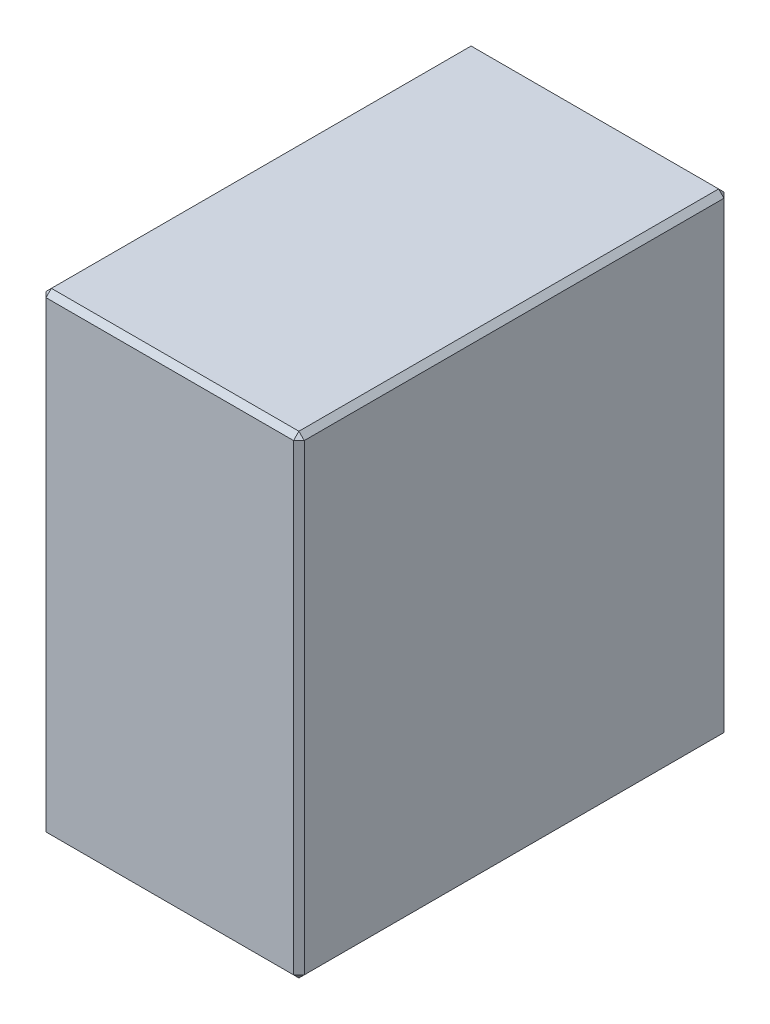
SolidWorks part; units mm, degrees
ref_plane "Front Plane" through (0, 0, 0) normal (0, 0, 1) x (1, 0, 0)
ref_plane "Top Plane" through (0, 0, 0) normal (0, 1, 0) x (1, 0, 0)
ref_plane "Right Plane" through (0, 0, 0) normal (1, 0, 0) x (0, 0, -1)
sketch "Sketch1" plane through (0, 0, 0) normal (1, 0, 0) x (0, 0, -1)
  line L0 (0, 0) -> (20, 0)
  line L1 (20, 0) -> (20, 22)
  line L2 (20, 22) -> (0, 22)
  line L3 (0, 22) -> (0, 0)
extrude "Boss-Extrude1" add sketch "Sketch1" against normal blind 12
hole_wizard "Hole1" positions "Sketch3" profile "Sketch2" legacy
sketch "Sketch3" plane through (0, 0, -20) normal (0, 0, -1) x (-1, 0, 0)
  point P0 (6, 17)
sketch "Sketch2" plane through (-6, 17, -20) normal (1, 0, 0) x (0, 1, 0)
  line L0 (0, 0) -> (0, 12.4781)
  line L1 (0, 12.4781) -> (2.46, 11)
  line L2 (2.46, 11) -> (2.46, 0)
  line L4 (2.46, 0) -> (0, 0)
  line L6 (0, 12.4781) -> (-2.46, 11) construction
  line L7 (0, -4.2442) -> (0, 117.3081) construction
  dimension "Diameter" = 4.92
  dimension "Depth" = 11
  dimension "Drill Angle" = 118
hole_wizard "M3.5 Clearance Hole1" positions "Sketch5" profile "Sketch4" hole size "M3.5" standard "ANSI Metric"
sketch "Sketch5" plane through (0, 0, 0) normal (0, -1, 0) x (-1, 0, 0)
  point P0 (6, 16)
  point P1 (6, 6)
sketch "Sketch4" plane through (-6, 0, -16) normal (1, 0, 0) x (0, 0, -1)
  line L0 (0, 0) -> (0, 13.2408)
  line L1 (0, 13.2408) -> (2.065, 12)
  line L2 (2.065, 12) -> (2.065, 0)
  line L5 (2.065, 0) -> (0, 0)
  line L10 (0, 13.2408) -> (-2.065, 12) construction
  line L11 (0, -6.35) -> (0, 107.95) construction
  dimension "Hole Dia." = 4.13
  dimension "Hole Depth" = 12
  dimension "Drill Angle" = 118
chamfer "Chamfer1" distance 0.25 angle 45 12 edges at (-6, 22, 0) (-12, 22, -10) (-6, 22, -20) (0, 22, -10) (-12, 11, 0) (0, 11, 0) (-6, 0, 0) (-12, 11, -20) (0, 11, -20) (-12, 0, -10) (0, 0, -10) (-6, 0, -20)
